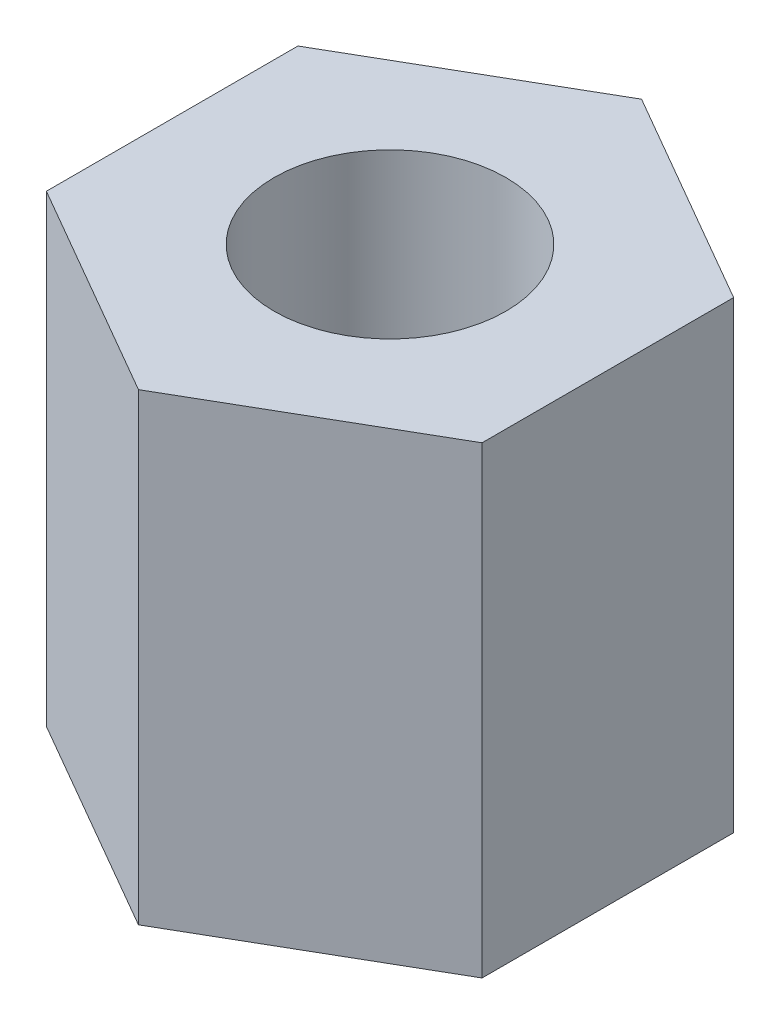
SolidWorks part; units mm, degrees
material "尼龙66"
ref_plane "前视基准面" through (0, 0, 0) normal (0, 0, 1) x (1, 0, 0)
ref_plane "上视基准面" through (0, 0, 0) normal (0, 1, 0) x (1, 0, 0)
ref_plane "右视基准面" through (0, 0, 0) normal (1, 0, 0) x (0, 0, -1)
other "Configuration Table"
sketch "草图1" plane through (0, 0, 0) normal (0, 1, 0) x (1, 0, 0)
  line L1 (0, 2.7135) -> (-2.35, 1.3568)
  line L2 (-2.35, 1.3568) -> (-2.35, -1.3568)
  line L3 (-2.35, -1.3568) -> (0, -2.7135)
  line L4 (0, -2.7135) -> (2.35, -1.3568)
  line L5 (2.35, -1.3568) -> (2.35, 1.3568)
  line L6 (2.35, 1.3568) -> (0, 2.7135)
  circle A0 centre (0, 0) radius 1.25
  circle A1 centre (0, 0) radius 2.35 construction
  dimension "D1" = 4.7
  dimension "D2" = 2.5
extrude "凸台-拉伸1" add sketch "草图1" along normal blind 5
